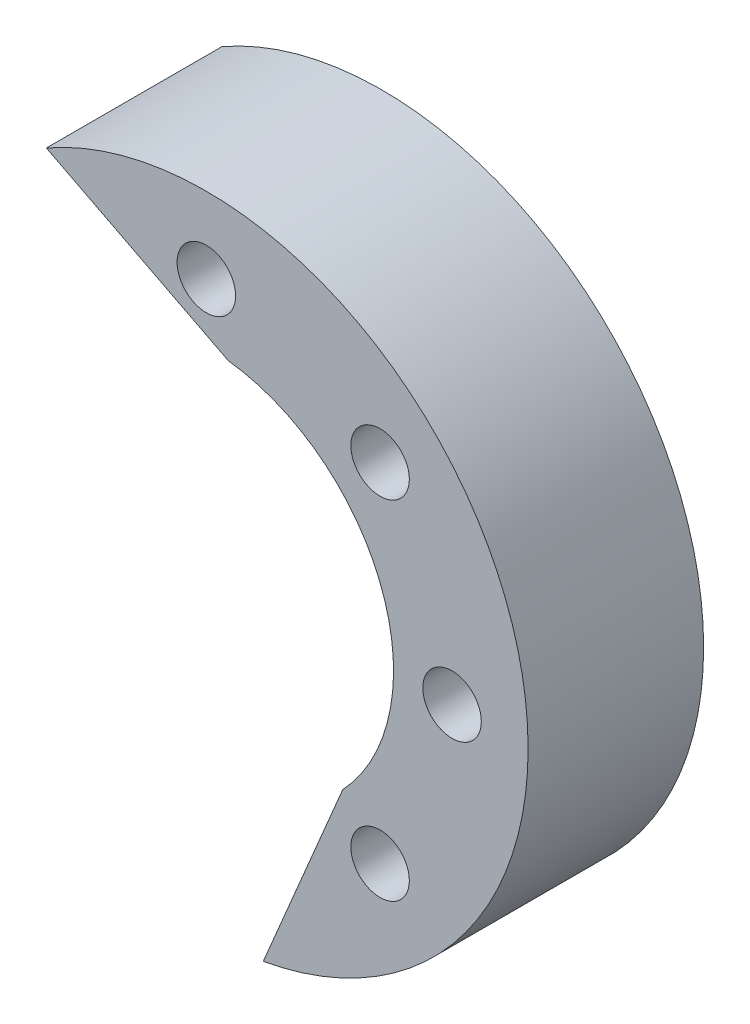
SolidWorks part; units mm, degrees
material "尼龙 101"
ref_plane "前视基准面" through (0, 0, 0) normal (0, 0, 1) x (1, 0, 0)
ref_plane "上视基准面" through (0, 0, 0) normal (0, 1, 0) x (1, 0, 0)
ref_plane "右视基准面" through (0, 0, 0) normal (1, 0, 0) x (0, 0, -1)
sketch "草图1" plane through (0, 0, 0) normal (0, 0, 1) x (1, 0, 0)
  line L0 (0, 55) -> (0, -55) construction
  line L1 (-55, 0) -> (55, 0) construction
  line L2 (0, 0) -> (-138.5641, 80) construction
  line L3 (0, 0) -> (-54.7232, -150.3508) construction
  line L4 (-27.3421, 47.7222) -> (3.7722, 31.7769)
  line L7 (9.73, -54.1325) -> (23.3155, -21.9178)
  arc A0 (9.73, -54.1325) -> (-27.3421, 47.7222) centre (0, 0) ccw
  arc A1 (23.3155, -21.9178) -> (3.7722, 31.7769) centre (0, 0) ccw
  circle A3 centre (-138.5641, 80) radius 22 construction
  circle A4 centre (0, 0) radius 30 construction
  circle A6 centre (-54.7232, -150.3508) radius 22 construction
  dimension "D1" = 110
  dimension "D2" = 64
  dimension "D4" = 160
  dimension "D5" = 44
  dimension "D6" = 60
  dimension "D8" = 160
  dimension "D9" = 44
  dimension "D3" = 150
  dimension "D7" = 20
extrude "凸台-拉伸1" add sketch "草图1" along normal blind 30
sketch "草图2" plane through (0, 0, 30) normal (0, 0, 1) x (1, 0, 0)
  circle A0 centre (0, 0) radius 42 construction
  point P3 (0, 42)
  point P6 (29.6985, 29.6985)
  point P7 (42, 0)
  point P8 (29.6985, -29.6985)
  point P9 (0, -42)
  point P10 (-29.6985, -29.6985)
  point P11 (-42, 0)
  point P12 (-29.6985, 29.6985)
  dimension "D1" = 84
  dimension "D2" = 8
hole_wizard "Ø4.2 (4.2) 直径孔1" positions "3D草图2" profile "草图6" hole size "Ø4.2" standard "GB" end condition through all
sketch3d "3D草图2"
  point P0 (0, 42, 30)
  point P3 (29.6985, 29.6985, 30)
  point P6 (42, 0, 30)
  point P9 (29.6985, -29.6985, 30)
sketch "草图6" plane through (0, 42, 30) normal (1, 0, 0) x (0, -1, 0)
  line L0 (0, 0) -> (0, 30)
  line L1 (0, 30) -> (2.1, 30)
  line L2 (2.1, 30) -> (2.1, 0)
  line L5 (2.1, 0) -> (0, 0)
  line L11 (0, -6.35) -> (0, 107.95) construction
  dimension "通孔孔直径" = 4.2
  dimension "通孔孔深度" = 30
sketch "草图7" plane through (0, 0, 30) normal (0, 0, 1) x (1, 0, 0)
  circle A0 centre (0, 42) radius 5
  circle A1 centre (29.6985, 29.6985) radius 5
  circle A2 centre (42, 0) radius 5
  circle A3 centre (29.6985, -29.6985) radius 5
  dimension "D1" = 10
  dimension "D2" = 10
  dimension "D3" = 10
  dimension "D4" = 10
extrude "切除-拉伸1" cut sketch "草图7" against normal blind 20
